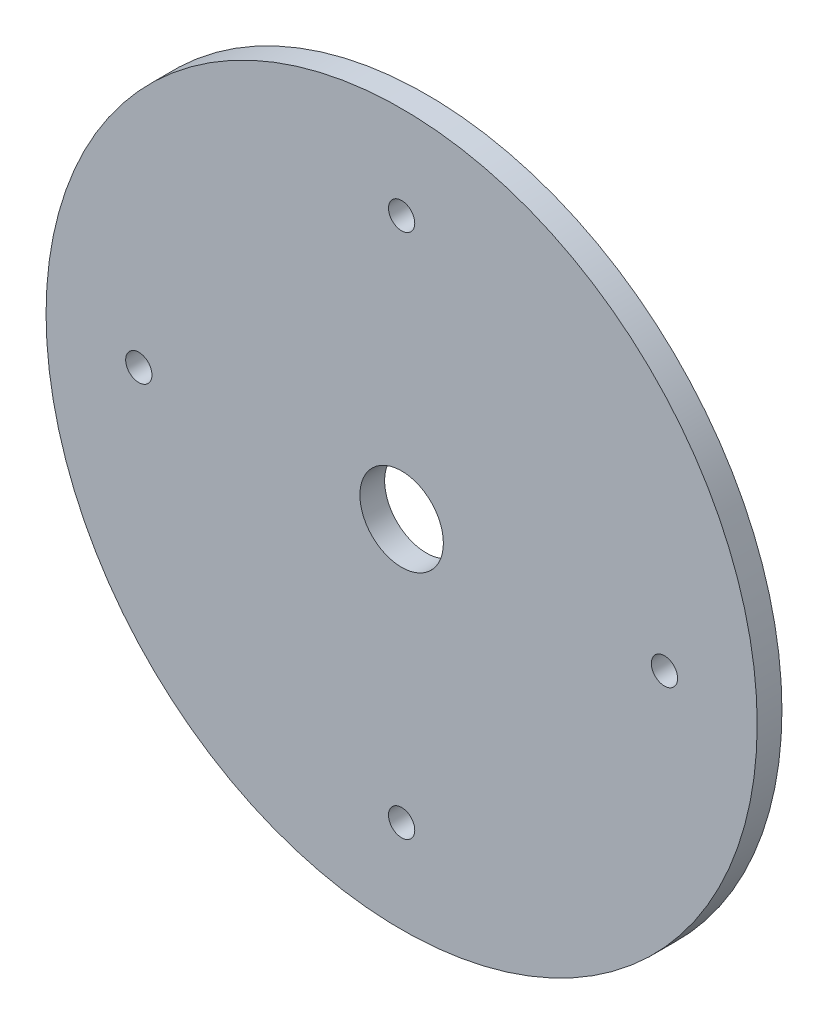
SolidWorks part; units mm, degrees
ref_plane "Front Plane" through (0, 0, 0) normal (0, 0, 1) x (1, 0, 0)
ref_plane "Top Plane" through (0, 0, 0) normal (0, 1, 0) x (1, 0, 0)
ref_plane "Right Plane" through (0, 0, 0) normal (1, 0, 0) x (0, 0, -1)
ref_plane "Plane1" through (0, 0, 462) normal (0, 0, 1) x (1, 0, 0)
sketch "Sketch1" plane through (0, 0, 462) normal (0, 0, 1) x (1, 0, 0)
  circle A0 centre (300, 300) radius 115
extrude "Boss-Extrude1" add sketch "Sketch1" along normal blind 8
sketch "Sketch2" plane through (0, 0, 470) normal (0, 0, 1) x (1, 0, 0)
  circle A0 centre (385, 300) radius 4.25
extrude "Cut-Extrude1" cut sketch "Sketch2" against normal blind 28
sketch "Sketch3" plane through (0, 0, 470) normal (0, 0, 1) x (1, 0, 0)
  circle A0 centre (215, 300) radius 4.25
extrude "Cut-Extrude2" cut sketch "Sketch3" against normal blind 28
sketch "Sketch4" plane through (0, 0, 470) normal (0, 0, 1) x (1, 0, 0)
  circle A0 centre (300, 385) radius 4.25
extrude "Cut-Extrude3" cut sketch "Sketch4" against normal blind 28
sketch "Sketch5" plane through (0, 0, 470) normal (0, 0, 1) x (1, 0, 0)
  circle A0 centre (300, 215) radius 4.25
extrude "Cut-Extrude4" cut sketch "Sketch5" against normal blind 28
sketch "Sketch6" plane through (0, 0, 470) normal (0, 0, 1) x (1, 0, 0)
  circle A0 centre (300, 300) radius 13.5
extrude "Cut-Extrude5" cut sketch "Sketch6" against normal blind 28
